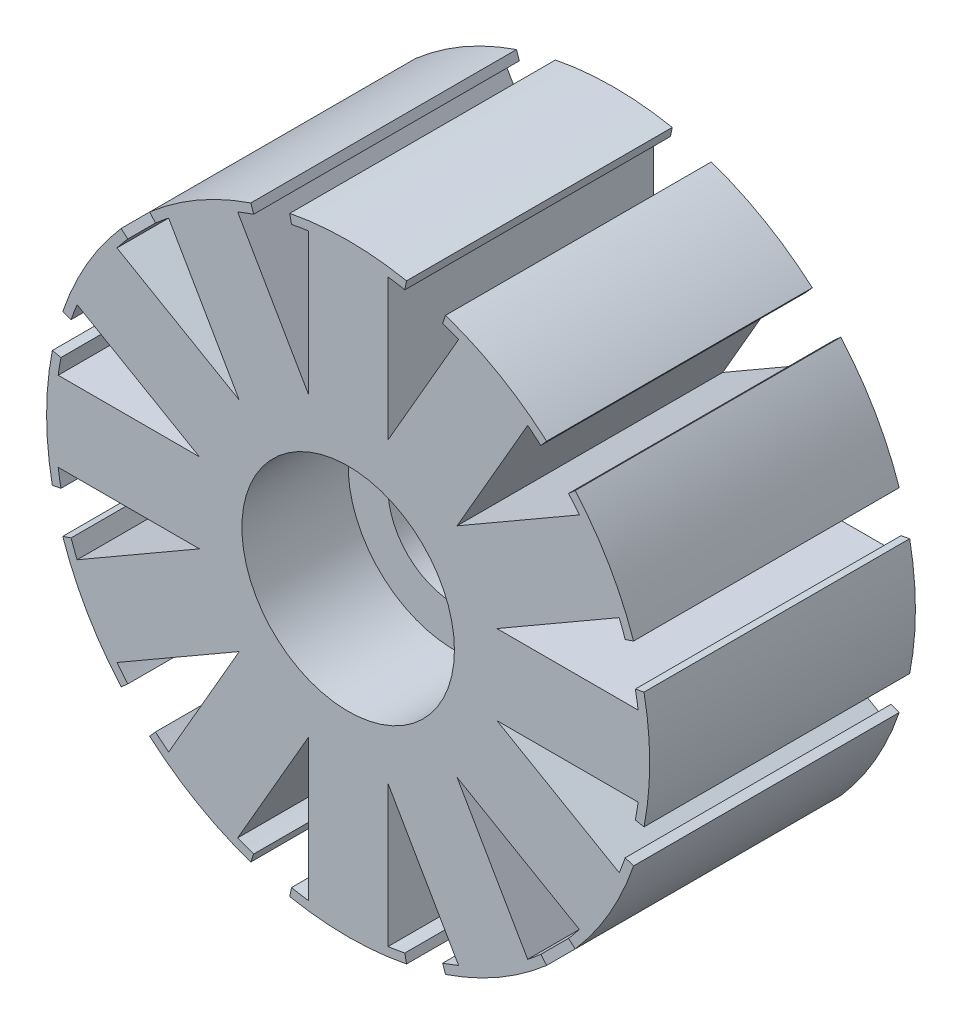
SolidWorks part; units mm, degrees
ref_plane "Front Plane" through (0, 0, 0) normal (0, 0, 1) x (1, 0, 0)
ref_plane "Top Plane" through (0, 0, 0) normal (0, 1, 0) x (1, 0, 0)
ref_plane "Right Plane" through (0, 0, 0) normal (1, 0, 0) x (0, 0, -1)
sketch "Sketch2" plane through (0, 0, 0) normal (0, 0, 1) x (1, 0, 0)
  line L0 (2.1331, 10.8082) -> (2.1977, 11.1352)
  line L1 (7.2514, 8.2936) -> (7.4708, 8.5445)
  line L3 (-1.5, 5.5981) -> (-1.5, 10.9141)
  line L4 (1.5, 5.5981) -> (4.158, 10.2019)
  line L5 (1.5, 10.9141) -> (1.5, 5.5981)
  line L6 (-2.1977, 11.1352) -> (-2.1331, 10.8082)
  line L7 (6.7561, 8.7019) -> (4.0981, 4.0981)
  line L8 (3.6644, 10.7422) -> (3.5568, 10.4267)
  line L9 (10.4267, 3.5568) -> (10.7422, 3.6644)
  line L10 (4.0981, 4.0981) -> (8.7019, 6.7561)
  line L11 (10.2019, 4.158) -> (5.5981, 1.5)
  line L12 (8.5445, 7.4708) -> (8.2936, 7.2514)
  line L13 (10.8082, -2.1331) -> (11.1352, -2.1977)
  line L14 (5.5981, 1.5) -> (10.9141, 1.5)
  line L15 (10.9141, -1.5) -> (5.5981, -1.5)
  line L16 (11.1352, 2.1977) -> (10.8082, 2.1331)
  line L17 (8.2936, -7.2514) -> (8.5445, -7.4708)
  line L18 (5.5981, -1.5) -> (10.2019, -4.158)
  line L19 (8.7019, -6.7561) -> (4.0981, -4.0981)
  line L20 (10.7422, -3.6644) -> (10.4267, -3.5568)
  line L21 (3.5568, -10.4267) -> (3.6644, -10.7422)
  line L22 (4.0981, -4.0981) -> (6.7561, -8.7019)
  line L23 (4.158, -10.2019) -> (1.5, -5.5981)
  line L24 (7.4708, -8.5445) -> (7.2514, -8.2936)
  line L25 (-2.1331, -10.8082) -> (-2.1977, -11.1352)
  line L26 (1.5, -5.5981) -> (1.5, -10.9141)
  line L27 (-1.5, -10.9141) -> (-1.5, -5.5981)
  line L28 (2.1977, -11.1352) -> (2.1331, -10.8082)
  line L29 (-7.2514, -8.2936) -> (-7.4708, -8.5445)
  line L30 (-1.5, -5.5981) -> (-4.158, -10.2019)
  line L31 (-6.7561, -8.7019) -> (-4.0981, -4.0981)
  line L32 (-3.6644, -10.7422) -> (-3.5568, -10.4267)
  line L33 (-10.4267, -3.5568) -> (-10.7422, -3.6644)
  line L34 (-4.0981, -4.0981) -> (-8.7019, -6.7561)
  line L35 (-10.2019, -4.158) -> (-5.5981, -1.5)
  line L36 (-8.5445, -7.4708) -> (-8.2936, -7.2514)
  line L37 (-10.8082, 2.1331) -> (-11.1352, 2.1977)
  line L38 (-5.5981, -1.5) -> (-10.9141, -1.5)
  line L39 (-10.9141, 1.5) -> (-5.5981, 1.5)
  line L40 (-11.1352, -2.1977) -> (-10.8082, -2.1331)
  line L41 (-8.2936, 7.2514) -> (-8.5445, 7.4708)
  line L42 (-5.5981, 1.5) -> (-10.2019, 4.158)
  line L43 (-8.7019, 6.7561) -> (-4.0981, 4.0981)
  line L44 (-10.7422, 3.6644) -> (-10.4267, 3.5568)
  line L45 (-3.5568, 10.4267) -> (-3.6644, 10.7422)
  line L46 (-4.0981, 4.0981) -> (-6.7561, 8.7019)
  line L47 (-4.158, 10.2019) -> (-1.5, 5.5981)
  line L48 (-7.4708, 8.5445) -> (-7.2514, 8.2936)
  arc A0 (-2.1977, 11.1352) -> (2.1977, 11.1352) centre (0, 0) cw
  arc A1 (-2.1331, 10.8082) -> (-1.5, 10.9141) centre (0, 0) cw
  arc A2 (2.1331, 10.8082) -> (1.5, 10.9141) centre (0, 0) ccw
  arc A3 (3.6644, 10.7422) -> (7.4708, 8.5445) centre (0, 0) cw
  arc A4 (3.5568, 10.4267) -> (4.158, 10.2019) centre (0, 0) cw
  arc A5 (7.2514, 8.2936) -> (6.7561, 8.7019) centre (0, 0) ccw
  arc A6 (8.5445, 7.4708) -> (10.7422, 3.6644) centre (0, 0) cw
  arc A7 (8.2936, 7.2514) -> (8.7019, 6.7561) centre (0, 0) cw
  arc A8 (10.4267, 3.5568) -> (10.2019, 4.158) centre (0, 0) ccw
  arc A9 (11.1352, 2.1977) -> (11.1352, -2.1977) centre (0, 0) cw
  arc A10 (10.8082, 2.1331) -> (10.9141, 1.5) centre (0, 0) cw
  arc A11 (10.8082, -2.1331) -> (10.9141, -1.5) centre (0, 0) ccw
  arc A12 (10.7422, -3.6644) -> (8.5445, -7.4708) centre (0, 0) cw
  arc A13 (10.4267, -3.5568) -> (10.2019, -4.158) centre (0, 0) cw
  arc A14 (8.2936, -7.2514) -> (8.7019, -6.7561) centre (0, 0) ccw
  arc A15 (7.4708, -8.5445) -> (3.6644, -10.7422) centre (0, 0) cw
  arc A16 (7.2514, -8.2936) -> (6.7561, -8.7019) centre (0, 0) cw
  arc A17 (3.5568, -10.4267) -> (4.158, -10.2019) centre (0, 0) ccw
  arc A18 (2.1977, -11.1352) -> (-2.1977, -11.1352) centre (0, 0) cw
  arc A19 (2.1331, -10.8082) -> (1.5, -10.9141) centre (0, 0) cw
  arc A20 (-2.1331, -10.8082) -> (-1.5, -10.9141) centre (0, 0) ccw
  arc A21 (-3.6644, -10.7422) -> (-7.4708, -8.5445) centre (0, 0) cw
  arc A22 (-3.5568, -10.4267) -> (-4.158, -10.2019) centre (0, 0) cw
  arc A23 (-7.2514, -8.2936) -> (-6.7561, -8.7019) centre (0, 0) ccw
  arc A24 (-8.5445, -7.4708) -> (-10.7422, -3.6644) centre (0, 0) cw
  arc A25 (-8.2936, -7.2514) -> (-8.7019, -6.7561) centre (0, 0) cw
  arc A26 (-10.4267, -3.5568) -> (-10.2019, -4.158) centre (0, 0) ccw
  arc A27 (-11.1352, -2.1977) -> (-11.1352, 2.1977) centre (0, 0) cw
  arc A28 (-10.8082, -2.1331) -> (-10.9141, -1.5) centre (0, 0) cw
  arc A29 (-10.8082, 2.1331) -> (-10.9141, 1.5) centre (0, 0) ccw
  arc A30 (-10.7422, 3.6644) -> (-8.5445, 7.4708) centre (0, 0) cw
  arc A31 (-10.4267, 3.5568) -> (-10.2019, 4.158) centre (0, 0) cw
  arc A32 (-8.2936, 7.2514) -> (-8.7019, 6.7561) centre (0, 0) ccw
  arc A33 (-7.4708, 8.5445) -> (-3.6644, 10.7422) centre (0, 0) cw
  arc A34 (-7.2514, 8.2936) -> (-6.7561, 8.7019) centre (0, 0) cw
  arc A35 (-3.5568, 10.4267) -> (-4.158, 10.2019) centre (0, 0) ccw
  point P101 (0, 0)
extrude "Boss-Extrude1" add sketch "Sketch2" along normal blind 10
sketch "Sketch3" plane through (0, 0, 10) normal (0, 0, 1) x (1, 0, 0)
  circle A0 centre (0, 0) radius 4
extrude "Cut-Extrude1" cut sketch "Sketch3" against normal blind 4
sketch "Sketch4" plane through (0, 0, 6) normal (0, 0, 1) x (1, 0, 0)
  circle A0 centre (0, 0) radius 2.5
extrude "Cut-Extrude2" cut sketch "Sketch4" against normal blind 10
